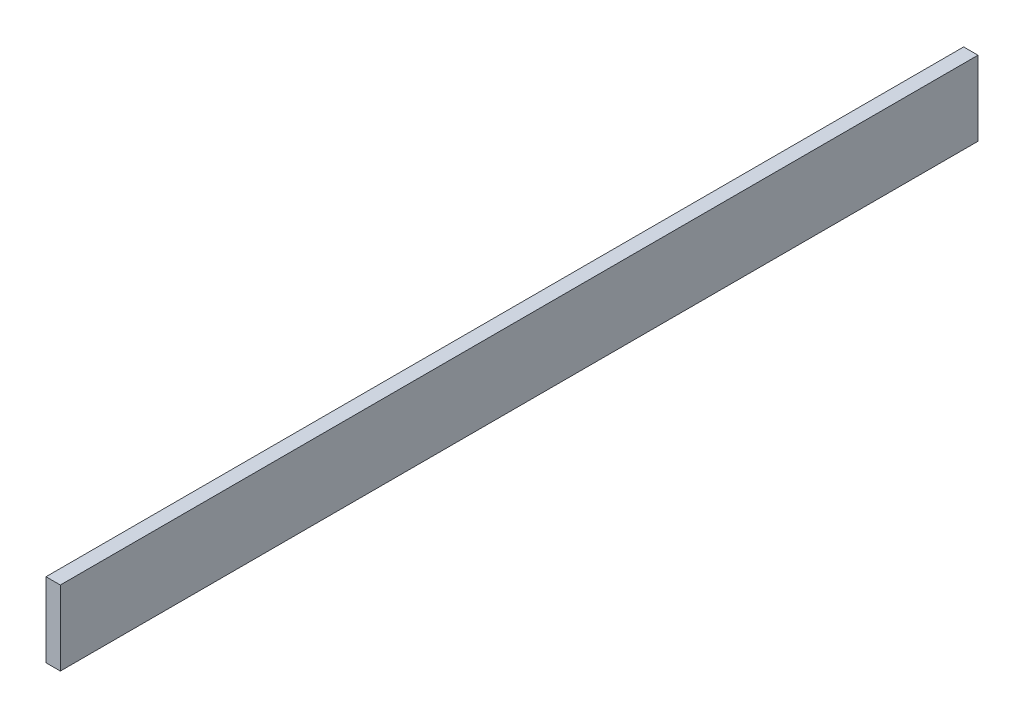
SolidWorks part; units mm, degrees
material "Chrome Stainless Steel"
ref_plane "Front Plane" through (0, 0, 0) normal (0, 0, 1) x (1, 0, 0)
ref_plane "Top Plane" through (0, 0, 0) normal (0, 1, 0) x (1, 0, 0)
ref_plane "Right Plane" through (0, 0, 0) normal (1, 0, 0) x (0, 0, -1)
sketch "Sketch1" plane through (0, 0, 0) normal (1, 0, 0) x (0, 0, -1)
  line L1 (0, 0) -> (406.4, 0)
  line L2 (0, 0) -> (0, 33.02)
  line L3 (0, 33.02) -> (406.4, 33.02)
  line L4 (406.4, 0) -> (406.4, 33.02)
  dimension "D1" = 406.4
  dimension "D2" = 33.02
extrude "Boss-Extrude1" add sketch "Sketch1" along normal blind 6.35
